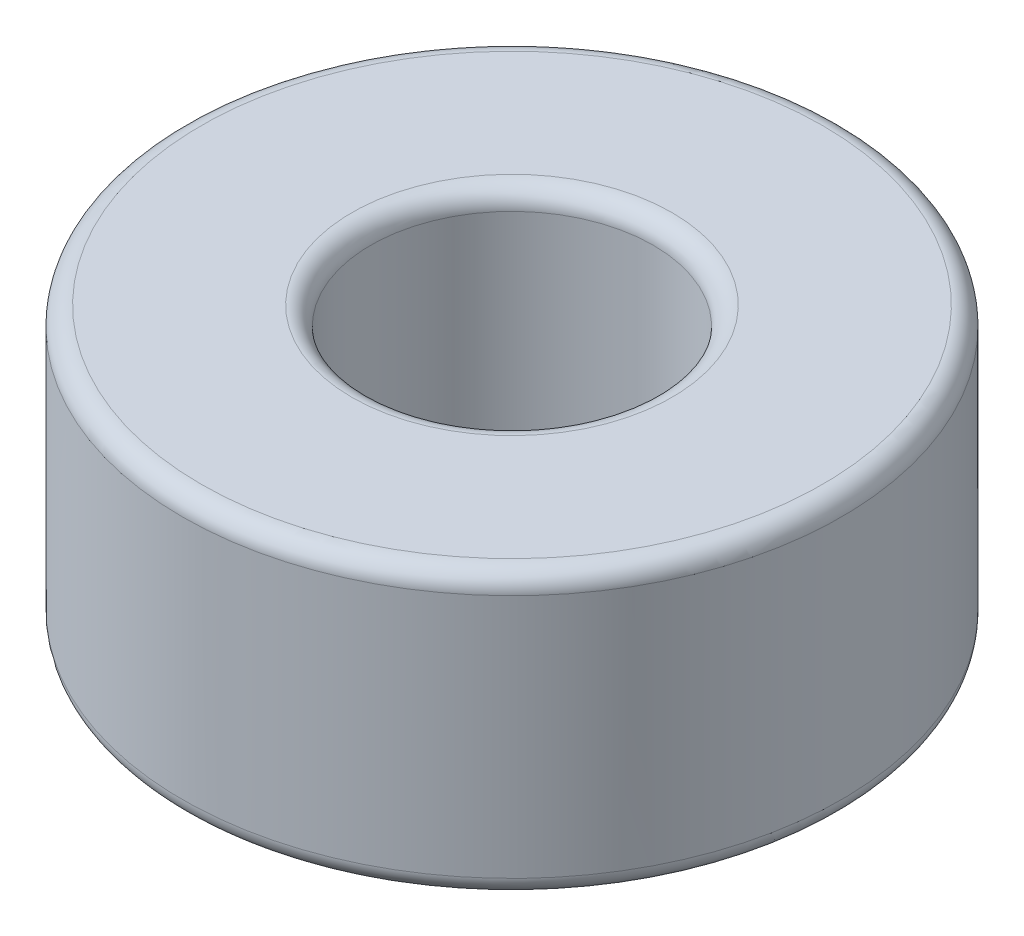
SolidWorks part; units mm, degrees
ref_plane "Plan de face" through (0, 0, 0) normal (0, 0, 1) x (1, 0, 0)
ref_plane "Plan de dessus" through (0, 0, 0) normal (0, 1, 0) x (1, 0, 0)
ref_plane "Plan de droite" through (0, 0, 0) normal (1, 0, 0) x (0, 0, -1)
sketch "Esquisse1" plane through (0, 0, 0) normal (0, 0, 1) x (1, 0, 0)
  line L0 (0, 0) -> (0, 9.3865) construction
  line L2 (1.5, 0) -> (3.5, 0)
  line L3 (1.5, 0) -> (1.5, 3)
  line L4 (1.5, 3) -> (3.5, 3)
  line L5 (3.5, 0) -> (3.5, 3)
  dimension "D1" = 3
  dimension "D2" = 7
  dimension "D3" = 3
revolve "Révolution1" add sketch "Esquisse1" angle 360 about L0
fillet "Congé1" radius 0.2 4 edges at (0, 0, -1.5) (0, 0, -3.5) (0, 3, -3.5) (0, 3, -1.5)
